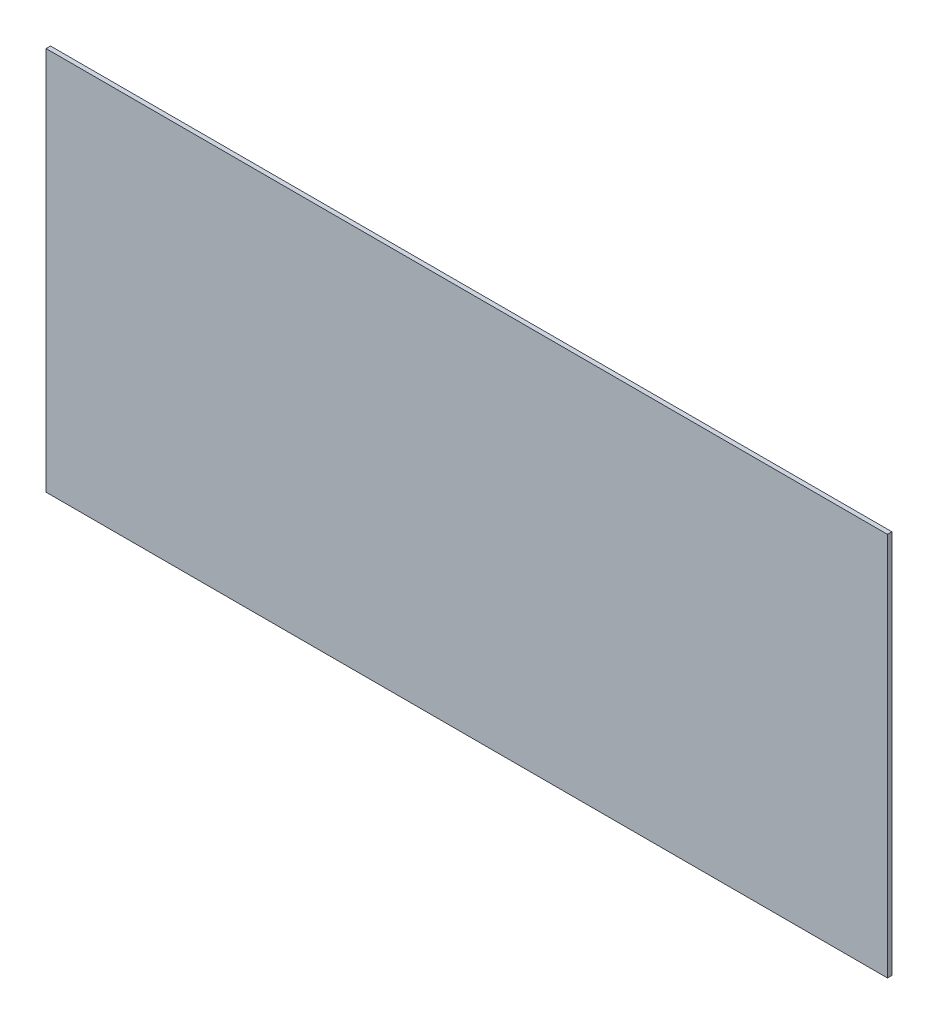
SolidWorks part; units mm, degrees
material "Acrylic (Medium-high impact)"
ref_plane "Front Plane" through (0, 0, 0) normal (0, 0, 1) x (1, 0, 0)
ref_plane "Top Plane" through (0, 0, 0) normal (0, 1, 0) x (1, 0, 0)
ref_plane "Right Plane" through (0, 0, 0) normal (1, 0, 0) x (0, 0, -1)
sketch "Sketch2" plane through (0, 0, 0) normal (0, 0, 1) x (1, 0, 0)
  line L1 (-674.6807, 225.195) -> (271.3193, 225.195)
  line L2 (-674.6807, 225.195) -> (-674.6807, -206.805)
  line L3 (-674.6807, -206.805) -> (271.3193, -206.805)
  line L4 (271.3193, 225.195) -> (271.3193, -206.805)
  dimension "D1" = 946
  dimension "D2" = 432
extrude "Boss-Extrude1" add sketch "Sketch2" along normal blind 5
